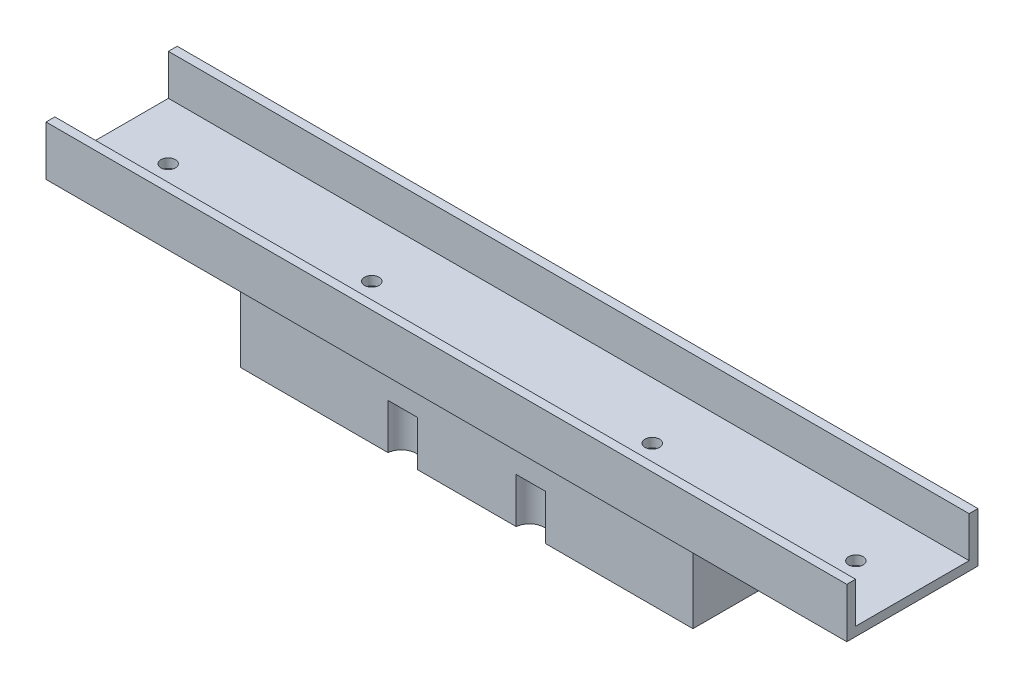
SolidWorks part; units mm, degrees
material "1060 Alloy"
ref_plane "Front" through (0, 0, 0) normal (0, 0, 1) x (1, 0, 0)
ref_plane "Top" through (0, 0, 0) normal (0, 1, 0) x (1, 0, 0)
ref_plane "Right" through (0, 0, 0) normal (1, 0, 0) x (0, 0, -1)
sketch "Sketch1" plane through (0, 0, 0) normal (1, 0, 0) x (0, 0, -1)
  line L0 (-14.5, 0) -> (14.5, 0)
  line L1 (-14.5, 0) -> (-14.5, 11)
  line L2 (-14.5, 11) -> (-12.55, 11)
  line L3 (-12.55, 11) -> (-12.55, 2)
  line L4 (-12.55, 2) -> (12.55, 2)
  line L5 (12.55, 2) -> (12.55, 11)
  line L6 (12.55, 11) -> (14.5, 11)
  line L7 (14.5, 11) -> (14.5, 0)
  dimension "D1" = 29
  dimension "D2" = 25.1
  dimension "D3" = 9
  dimension "D4" = 2
extrude "Boss-Extrude1" add sketch "Sketch1" along normal mid plane 177
sketch "Sketch3" plane through (0, 0, 0) normal (0, -1, 0) x (1, 0, 0)
  line L1 (50, -10) -> (-50, -10)
  line L2 (50, -10) -> (50, 10)
  line L3 (50, 10) -> (-50, 10)
  line L4 (-50, -10) -> (-50, 10)
  line L5 (50, -10) -> (-50, 10) construction
  line L6 (50, 10) -> (-50, -10) construction
  point P0 (0, 0)
  dimension "D1" = 100
  dimension "D2" = 20
extrude "Boss-Extrude2" add sketch "Sketch3" along normal blind 19
sketch "Sketch2" plane through (0, 0, 0) normal (0, -1, 0) x (1, 0, 0)
  line L0 (-88.5, 0) -> (88.5, 0) construction
  line L1 (-88.5, 14.5) -> (-88.5, -14.5) construction
  line L2 (88.5, 14.5) -> (88.5, -14.5) construction
  line L3 (0, 14.5) -> (0, -14.5) construction
  line L4 (88.5, 14.5) -> (-88.5, 14.5) construction
  line L5 (88.5, -14.5) -> (-88.5, -14.5) construction
  circle A0 centre (76, 0) radius 1.6
  circle A1 centre (31, 0) radius 1.6
  circle A2 centre (-31, 0) radius 1.6
  circle A3 centre (-76, 0) radius 1.6
  dimension "D1" = 45
  dimension "D3" = 3.2
  dimension "D2" = 12.5
extrude "Cut-Extrude1" cut sketch "Sketch2" against normal through all and the other way blind 16
sketch "Sketch4" plane through (0, -19, 0) normal (0, -1, 0) x (1, 0, 0)
  circle A0 centre (-31, 0) radius 3
  circle A1 centre (31, 0) radius 3
  dimension "D1" = 6
extrude "Cut-Extrude2" cut sketch "Sketch4" against normal up to surface (19 mm away) up to face at (-76, 0, 1.6)
hole_wizard "M3x0.5 Tapped Hole1" positions "Sketch6" profile "Sketch8" tap size "M3x0.5" standard "ANSI Metric"
sketch "Sketch6" plane through (0, -19, 0) normal (0, -1, 0) x (-1, 0, 0)
  line L1 (26.5, 6) -> (-26.5, 6) construction
  line L2 (26.5, 6) -> (26.5, -6) construction
  line L3 (26.5, -6) -> (-26.5, -6) construction
  line L4 (-26.5, 6) -> (-26.5, -6) construction
  line L5 (26.5, 6) -> (-26.5, -6) construction
  line L6 (26.5, -6) -> (-26.5, 6) construction
  point P2 (-26.5, -6)
  point P5 (26.5, 6)
  point P6 (26.5, -6)
  point P7 (-26.5, 6)
  point P79 (0, 0)
  dimension "D1" = 12
  dimension "D2" = 53
sketch "Sketch8" plane through (26.5, -19, 6) normal (1, 0, 0) x (0, 0, -1)
  line L0 (0, 0) -> (0, 8.2511)
  line L1 (0, 8.2511) -> (1.25, 7.5)
  line L2 (1.25, 7.5) -> (1.25, 0.275)
  line L3 (1.25, 0.275) -> (1.525, 0)
  line L5 (1.525, 0) -> (0, 0)
  line L6 (-1.25, 0.275) -> (-1.525, 0) construction
  line L10 (0, 8.2511) -> (-1.25, 7.5) construction
  line L11 (0, -6.35) -> (0, 107.95) construction
  dimension "Tap Drill Dia." = 2.5
  dimension "Tap Drill Depth" = 7.5
  dimension "Near C'Sink Dia." = 3.05
  dimension "Near C'Sink Angle" = 90
  dimension "Drill Angle" = 118
cosmetic thread "Hole Thread1" parameters "D1"=6, "D2"=3
cosmetic thread "Hole Thread2" parameters "D1"=6, "D2"=3
cosmetic thread "Hole Thread3" parameters "D1"=6, "D2"=3
cosmetic thread "Hole Thread4" parameters "D1"=6, "D2"=3
sketch "Sketch9" plane through (0, -19, 0) normal (0, -1, 0) x (1, 0, 0)
  line L1 (14.1587, -10.285) -> (-14.1587, -10.285) construction
  line L2 (14.1587, -10.285) -> (14.1587, 10.285) construction
  line L3 (14.1587, 10.285) -> (-14.1587, 10.285) construction
  line L4 (-14.1587, -10.285) -> (-14.1587, 10.285) construction
  line L5 (14.1587, -10.285) -> (-14.1587, 10.285) construction
  line L6 (14.1587, 10.285) -> (-14.1587, -10.285) construction
  circle A0 centre (0, 0) radius 17.5 construction
  circle A1 centre (14.1587, -10.285) radius 3.25
  circle A2 centre (-14.1587, -10.285) radius 3.25
  circle A3 centre (-14.1587, 10.285) radius 3.25
  circle A4 centre (14.1587, 10.285) radius 3.25
  dimension "D1" = 35
  dimension "D3" = 6.5
  dimension "D2" = 20.57
extrude "Cut-Extrude3" cut sketch "Sketch9" against normal blind 10
